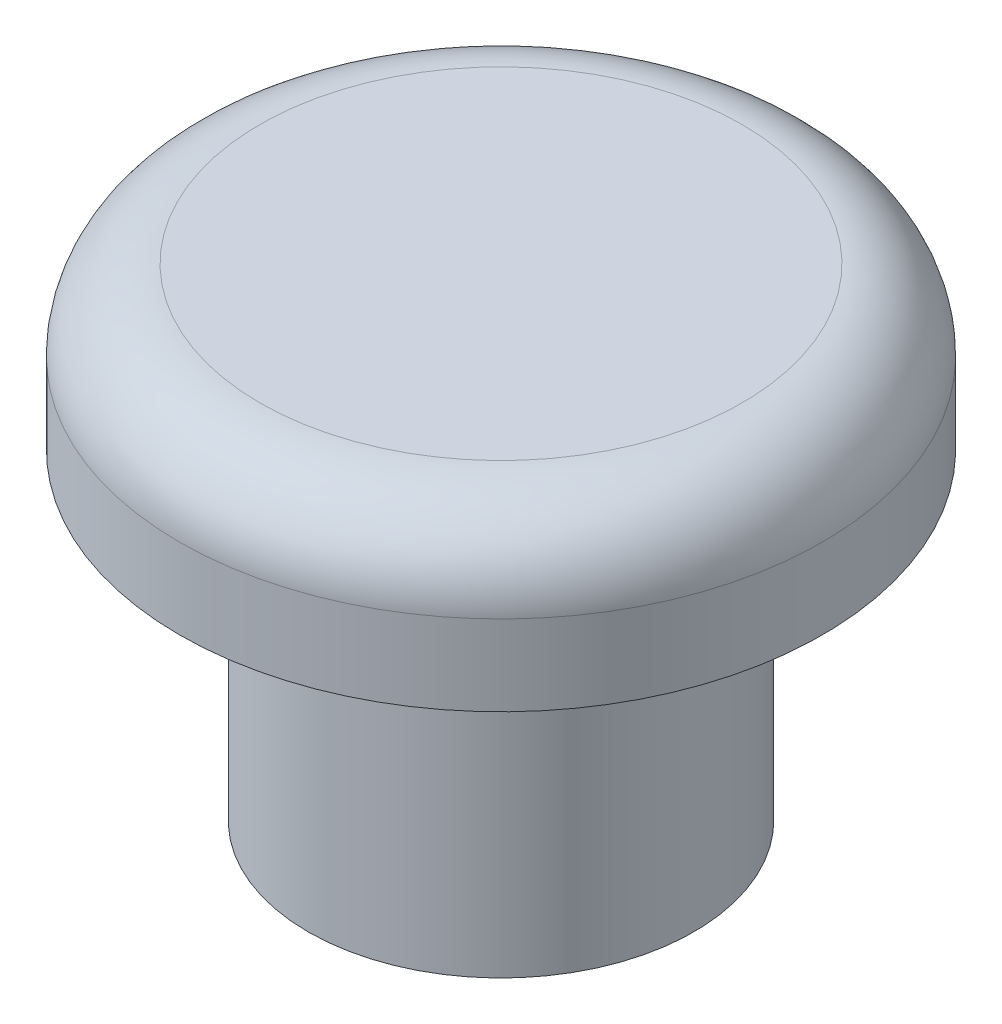
SolidWorks part; units mm, degrees
ref_plane "Front Plane" through (0, 0, 0) normal (0, 0, 1) x (1, 0, 0)
ref_plane "Top Plane" through (0, 0, 0) normal (0, 1, 0) x (1, 0, 0)
ref_plane "Right Plane" through (0, 0, 0) normal (1, 0, 0) x (0, 0, -1)
sketch "Sketch1" plane through (0, 0, 0) normal (0, 1, 0) x (1, 0, 0)
  circle A0 centre (0, 0) radius 4.075
  circle A1 centre (0, 0) radius 6
  dimension "D1" = 8.15
  dimension "D2" = 12
extrude "Boss-Extrude1" add sketch "Sketch1" along normal blind 10
sketch "Sketch2" plane through (0, 10, 0) normal (0, 1, 0) x (1, 0, 0)
  circle A0 centre (0, 0) radius 10
  circle A1 centre (0, 0) radius 6 construction
  dimension "D1" = 4
extrude "Boss-Extrude2" add sketch "Sketch2" along normal blind 5
fillet "Fillet1" radius 2.5
